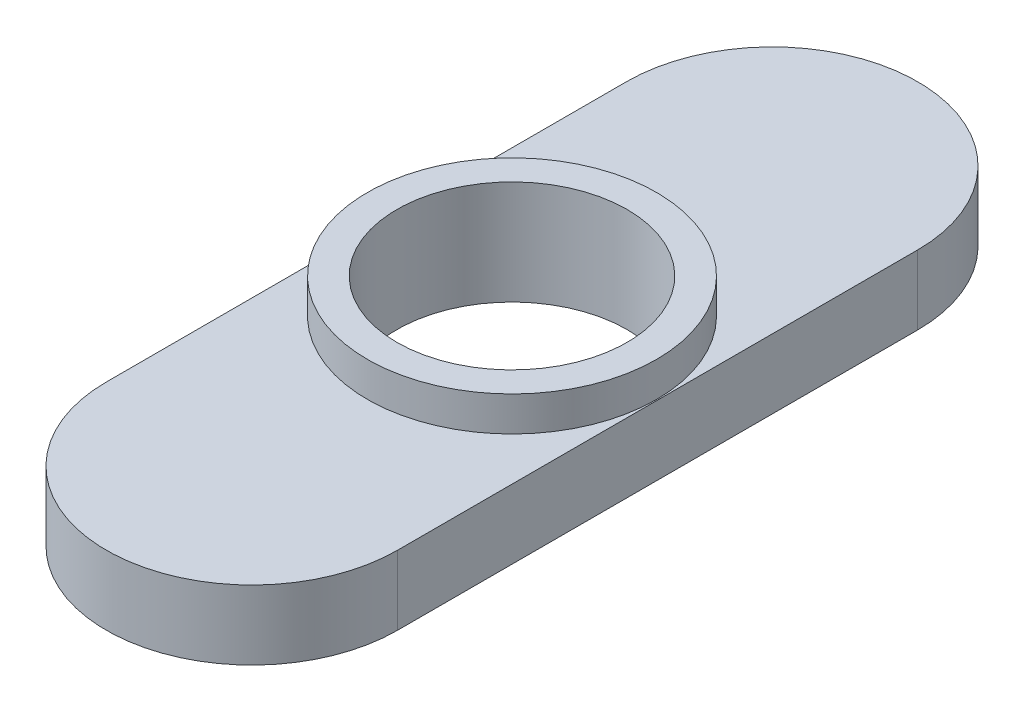
SolidWorks part; units mm, degrees
ref_plane "Front Plane" through (0, 0, 0) normal (0, 0, 1) x (1, 0, 0)
ref_plane "Top Plane" through (0, 0, 0) normal (0, 1, 0) x (1, 0, 0)
ref_plane "Right Plane" through (0, 0, 0) normal (1, 0, 0) x (0, 0, -1)
sketch "Sketch1" plane through (0, 0, 0) normal (0, 1, 0) x (1, 0, 0)
  line L0 (0, 9.525) -> (0, -9.525) construction
  line L1 (5.334, 9.525) -> (5.334, -9.525)
  line L2 (-5.334, 9.525) -> (-5.334, -9.525)
  arc A0 (5.334, 9.525) -> (-5.334, 9.525) centre (0, 9.525) ccw
  arc A1 (-5.334, -9.525) -> (5.334, -9.525) centre (0, -9.525) ccw
  point P2 (0, 0)
  dimension "D2" = 9.525
  dimension "D1" = 10.668
extrude "Boss-Extrude1" add sketch "Sketch1" along normal blind 2.54 contours A0 L2 A1 L1
sketch "Sketch2" plane through (0, 2.54, 0) normal (0, 1, 0) x (1, 0, 0)
  circle A0 centre (0, 0) radius 4.2164
  dimension "D1" = 8.4328
extrude "Cut-Extrude1" cut sketch "Sketch2" against normal blind 2.54 contours A0
sketch "Sketch3" plane through (0, 2.54, 0) normal (0, 1, 0) x (1, 0, 0)
  circle A0 centre (0, 0) radius 4.2164
extrude "Extrude-Thin1" add sketch "Sketch3" along normal blind 1.27 thin
